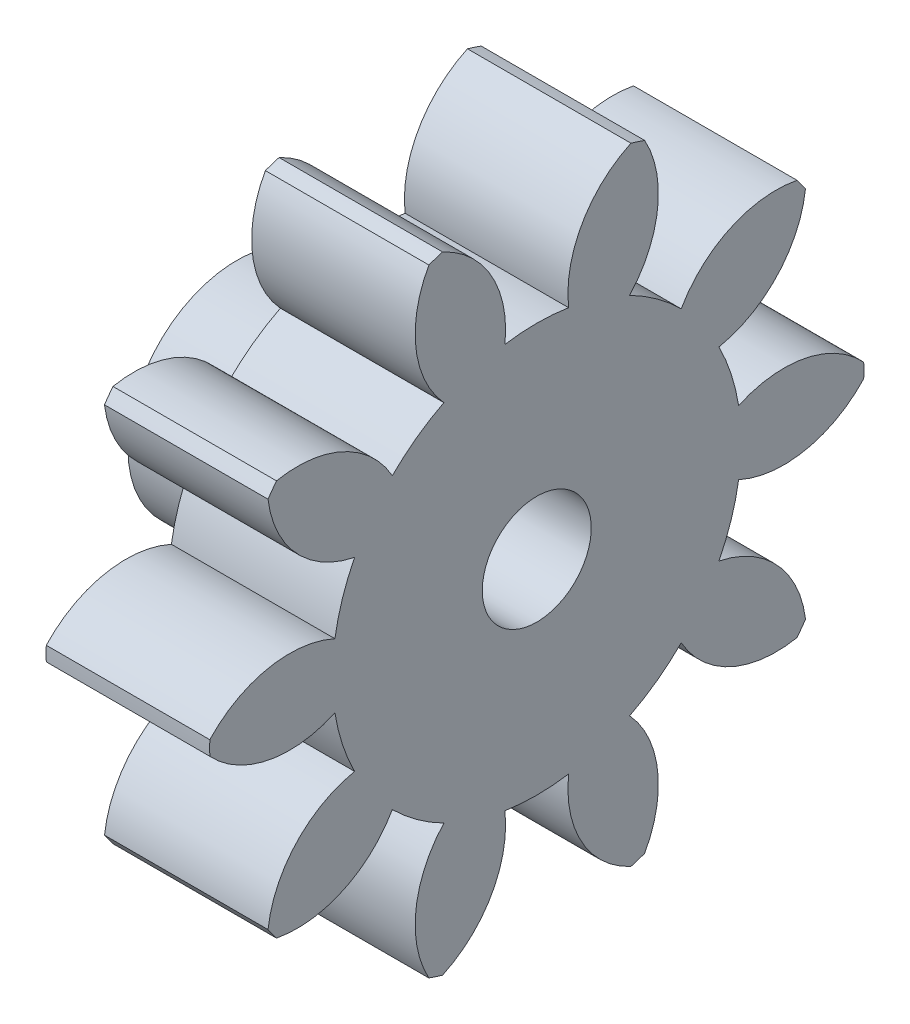
SolidWorks part; units mm, degrees
ref_plane "Plane1" through (0, 0, 0) normal (0, 0, 1) x (1, 0, 0)
ref_plane "Plane2" through (0, 0, 0) normal (0, 1, 0) x (1, 0, 0)
ref_plane "Plane3" through (0, 0, 0) normal (1, 0, 0) x (0, 0, -1)
sketch "HoldingSke" plane through (0, 0, 0) normal (0, 1, 0) x (1, 0, 0)
  line L0 (0, 0) -> (0.2462, -0.0434)
  line L1 (-15, 0) -> (100, 0) construction
  line L2 (0, 0) -> (-2.1039, 2.3779)
  line L3 (0, 0) -> (-11.863, 4.5341)
  line L4 (0, 0) -> (8.5048, 1.4996)
  line L5 (0, 0) -> (-9.3695, -3.4946)
  line L6 (0, 0) -> (-9.9476, -6.7116)
  line L7 (-2.1039, 2.3779) -> (0.4791, 14.0966)
  line L8 (-76.2, 54.61) -> (-74.8, 54.61)
  line L9 (-71.009, 38.7566) -> (-53.1078, 45.2721)
  line L10 (-76.2, 71.12) -> (104.1128, 71.12)
  line L11 (0, 0) -> (-12, 0)
  line L12 (-76.2, 101.6) -> (-76.073, 101.6)
  line L13 (24.9733, 27.94) -> (52.9518, 28.4284)
  line L14 (24.9733, 27.94) -> (24.9743, 27.94)
  line L15 (24.9733, 27.94) -> (100.4006, 29.5858)
  line L16 (-63.627, -4) -> (-12.827, -4)
  circle A0 centre (0, 0) radius 4
  circle A1 centre (0, 0) radius 8
  circle A2 centre (0, 0) radius 8
  circle A3 centre (0, 0) radius 4
  dimension "MHD" = 16
  dimension "Hub_dia" = 16
  dimension "Bore" = 8
  dimension "MBD" = 8
  dimension "Num_teeth" = 10
  dimension "Pitch" = 0.25
  dimension "Overall_len" = 10
  dimension "Show_teeth" = 10
  dimension "Thickness" = 12
  dimension "OAL" = 12.0001
  dimension "T_dim" = 1.4
  dimension "Ap" = 20
  dimension "H" = 19.05
  dimension "Pitch_radius" = 180.3128
  dimension "Width" = 12
  dimension "Backlash" = 0.127
  dimension "Addendum_fac" = 1
  dimension "Dedendum_fac" = 1.25
  dimension "Clearance_fac" = 0.25
  dimension "Dedendum_add" = 0.001
  dimension "Module" = 4
sketch "BasProSke" plane through (0, 0, 0) normal (0, 1, 0) x (1, 0, 0)
  line L0 (-10, 0) -> (60, 0) construction
  line L1 (0, 0) -> (0, 24)
  line L2 (0, 0) -> (12, 0)
  line L3 (12, 0) -> (12, 24)
  line L4 (12, 24) -> (0, 24)
  dimension "Thickness" = 12
  dimension "Diameter" = 48
revolve "Base-Revolve" add sketch "BasProSke" angle 360 about L0
sketch "TooCutSke" plane through (0, 0, 0) normal (1, 0, 0) x (0, 0, -1)
  line L1 (0, 0) -> (0, 107) construction
  line L2 (0, 0) -> (-3.3505, 19.7173) construction
  line L3 (0, 0) -> (-12.2295, 37.6384) construction
  line L4 (-3.3505, 19.7173) -> (-6.1147, 18.8192) construction
  arc A0 (2.338, 14.8157) -> (-2.338, 14.8157) centre (0, 0) ccw
  arc A1 (6.9466, 22.9992) -> (-6.9466, 22.9992) centre (0, 0) ccw
  circle A2 centre (0, 0) radius 20 construction
  circle A3 centre (0, 0) radius 18.7939 construction
  arc A4 (-2.338, 14.8157) -> (-6.9466, 22.9992) centre (-10.2857, 15.7294) ccw
  arc A5 (6.9466, 22.9992) -> (2.338, 14.8157) centre (10.2857, 15.7294) ccw
  dimension "Root_dia" = 29.998
  dimension "Overcut_dia" = 48.0508
  dimension "Pitch_dia" = 40
  dimension "Base_dia" = 37.5877
  dimension "Flank_rad" = 8
  dimension "Half_ang" = 18
  dimension "Half_CT" = 2.9064
extrude "ToothCut" cut sketch "TooCutSke" along normal through all
fillet "Breaks" [suppressed] radius 0.08
fillet "RootFillets" [suppressed] radius 1.001
pattern_circular "TeethCuts" count 10 every 36 about axis through (-10, 0, 0) along (1, 0, 0) of "ToothCut", "RootFillets", "Breaks"
sketch "HubNeaOneSke" plane through (0, 0, 0) normal (-1, 0, 0) x (0, 0, 1)
  circle A0 centre (0, 0) radius 8
  dimension "Diameter" = 16
extrude "HubNearOne" add sketch "HubNeaOneSke" along normal blind 38.0001
sketch "HubNeaBotSke" plane through (0, 0, 0) normal (-1, 0, 0) x (0, 0, 1)
  circle A0 centre (0, 0) radius 8
  dimension "Diameter" = 16
extrude "HubNearBoth" [suppressed] add sketch "HubNeaBotSke" along normal blind 19
ref_plane "FarPln" through (12, 0, 0) normal (1, 0, 0) x (0, 0, -1)
sketch "HubFarSke" plane through (12, 0, 0) normal (1, 0, 0) x (0, 0, -1)
  circle A0 centre (0, 0) radius 8
  dimension "Diameter" = 16
extrude "HubFar" [suppressed] add sketch "HubFarSke" along normal blind 19
sketch "BorSke" plane through (0, 0, 0) normal (1, 0, 0) x (0, 0, -1)
  circle A0 centre (0, 0) radius 4
  dimension "Diameter" = 8
extrude "Bore" cut sketch "BorSke" along normal mid plane 24.0001
sketch "KeySke" plane through (0, 0, 0) normal (1, 0, 0) x (0, 0, -1)
  line L0 (-1.5, 0) -> (-1.5, 5.4)
  line L1 (-1.5, 5.4) -> (1.5, 5.4)
  line L2 (1.5, 5.4) -> (1.5, 0)
  line L3 (0, 0) -> (0, 34) construction
  line L4 (-1.5, 0) -> (1.5, 0)
  dimension "Offset" = 5.4
  dimension "Width" = 3
extrude "Keyway" [suppressed] cut sketch "KeySke" along normal mid plane 24.0001
pattern_circular "Keyway2" [suppressed] count 2 every 90 about axis through (-10, 0, 0) along (1, 0, 0)
ref_plane "Plane4" through (-10, 0, 0) normal (-1, 0, 0) x (0, 0, 1)
sketch "Sketch1" plane through (-10, 0, 0) normal (-1, 0, 0) x (0, 0, 1)
  circle A0 centre (0, 0) radius 10.2707
extrude "Cut-Extrude1" cut sketch "Sketch1" along normal blind 43
equation "' \"Module@HoldingSke\" = 6.35"
equation "' \"Num_teeth@HoldingSke\" = 12"
equation "' \"Ap@HoldingSke\" =  20"
equation "' \"Ap@HoldingSke\" = 20"
equation "' \"Width@HoldingSke\" = 0.5 * 25.4"
equation "' \"Hub_dia@HoldingSke\"= 1 * 25.4"
equation "' \"Hub_dia@HoldingSke\" = 1 * 25.4"
equation "' \"Overall_len@HoldingSke\" = 1.0 * 25.4"
equation "' \"Bore@HoldingSke\" = 0.75 * 25.4"
equation "' \"T_dim@HoldingSke\" = 0.1 * 25.4"
equation "' \"Width@KeySke\" = 0.25 * 25.4"
equation "' \"Show_teeth@HoldingSke\" = 13"
equation "' \"Backlash@HoldingSke\" = 0.009 * 25.4"
equation "' \"Addendum_fac@HoldingSke\" = 1.0"
equation "' \"Dedendum_fac@HoldingSke\" = 1.25"
equation "' \"Dedendum_add@HoldingSke\" = 0.00005 * 25.4"
equation "' \"Clearance_fac@HoldingSke\" = 0.25"
equation "\"Pitch@HoldingSke\" = 1 / \"Module@HoldingSke\""
equation "\"Overcut_dia@TooCutSke\" = (\"Num_teeth@HoldingSke\" + 2 * \"Addendum_fac@HoldingSke\") / \"Pitch@HoldingSke\" + 0.002 * 25.4"
equation "\"Pitch_dia@TooCutSke\" = \"Num_teeth@HoldingSke\" / \"Pitch@HoldingSke\""
equation "\"Base_dia@TooCutSke\" = \"Num_teeth@HoldingSke\" / \"Pitch@HoldingSke\" * cos((\"Ap@HoldingSke\"  * 3.14159265 / 180))"
equation "\"Root_dia@TooCutSke\" = (\"Num_teeth@HoldingSke\" + 2) / \"Pitch@HoldingSke\" - 2 * (\"Addendum_fac@HoldingSke\" + \"Dedendum_fac@HoldingSke\") / \"Pitch@HoldingSke\" - \"Dedendum_add@HoldingSke\" * 2"
equation "\"Half_ang@TooCutSke\" = 180 / \"Num_teeth@HoldingSke\""
equation "\"Half_CT@TooCutSke\" = \"Num_teeth@HoldingSke\" / \"Pitch@HoldingSke\" * sin((3.14159265 / 2 / \"Num_teeth@HoldingSke\")) / 2 - 7 * \"Backlash@HoldingSke\" / 4"
equation "\"Flank_rad@TooCutSke\" = \"Num_teeth@HoldingSke\" / \"Pitch@HoldingSke\" / 5"
equation "\"Radius@RootFillets\" = \"Clearance_fac@HoldingSke\" / \"Pitch@HoldingSke\" + \"Dedendum_add@HoldingSke\""
equation "\"Break_rad@Breaks\" = 0.02 / \"Pitch@HoldingSke\""
equation "\"Thickness@HoldingSke\" = \"Width@HoldingSke\""
equation "\"OAL@HoldingSke\" = \"Thickness@HoldingSke\""
equation "\"MHD@HoldingSke\" = (\"Num_teeth@HoldingSke\" + 2) / \"Pitch@HoldingSke\" - 2 * (\"Addendum_fac@HoldingSke\" + \"Dedendum_fac@HoldingSke\")  / \"Pitch@HoldingSke\" - \"Dedendum_add@HoldingSke\" * 2"
equation "\"MBD@HoldingSke\" = (\"Num_teeth@HoldingSke\" + 2) / \"Pitch@HoldingSke\" - 2 * (\"Addendum_fac@HoldingSke\" + \"Dedendum_fac@HoldingSke\")  / \"Pitch@HoldingSke\" - \"Dedendum_add@HoldingSke\" * 2 - 0.002 * 25.4"
equation "\"MHD@HoldingSke\" = ((sgn( \"MHD@HoldingSke\" - \"Hub_dia@HoldingSke\" )-1)*( \"MHD@HoldingSke\" - \"Hub_dia@HoldingSke\" ))/-2+ \"Hub_dia@HoldingSke\""
equation "\"MBD@HoldingSke\" = ((sgn( \"MBD@HoldingSke\" - \"Bore@HoldingSke\" )-1)*( \"MBD@HoldingSke\" - \"Bore@HoldingSke\" ))/-2+ \"Bore@HoldingSke\""
equation "\"OAL@HoldingSke\" = ((sgn( \"OAL@HoldingSke\" - \"Overall_len@HoldingSke\" )+1)*( \"OAL@HoldingSke\" - \"Overall_len@HoldingSke\" ))/2 + \"Overall_len@HoldingSke\" + 0.000002 * 25.4"
equation "\"Num_teeth@TeethCuts\" = int( \"Show_teeth@HoldingSke\" ) + 1"
equation "\"Num_teeth@TeethCuts\" = ((sgn( \"Num_teeth@TeethCuts\" - \"Num_teeth@HoldingSke\" )-1)*( \"Num_teeth@TeethCuts\" - \"Num_teeth@HoldingSke\" ))/-2+ \"Num_teeth@HoldingSke\""
equation "\"Num_teeth@TeethCuts\" = ((sgn( \"Num_teeth@TeethCuts\" - 2.0)+1)*( \"Num_teeth@TeethCuts\" - 2.0))/2 +2.0"
equation "\"Angle@TeethCuts\" = 360.0 / \"Num_teeth@HoldingSke\""
equation "\"Diameter@BasProSke\" = (\"Num_teeth@HoldingSke\" + 2 * \"Addendum_fac@HoldingSke\") / \"Pitch@HoldingSke\""
equation "\"Thickness@BasProSke\"  = \"Thickness@HoldingSke\""
equation "' \"Fillet_rad@BasProSke\" =  \"Thickness@HoldingSke\" * 0.05"
equation "' \"Fillet_rad@BasProSke\" = \"Thickness@HoldingSke\" * 0.05"
equation "\"MHD@HoldingSke\" = ((sgn( \"MHD@HoldingSke\" - \"Root_dia@TooCutSke\" )-1)*( \"MHD@HoldingSke\" - \"Root_dia@TooCutSke\" ))/-2+ \"Root_dia@TooCutSke\""
equation "\"Diameter@HubNeaOneSke\" = \"MHD@HoldingSke\""
equation "\"Length@HubNearOne\" = \"OAL@HoldingSke\" - \"Thickness@BasProSke\""
equation "\"Diameter@HubNeaBotSke\" = \"MHD@HoldingSke\""
equation "\"Length@HubNearBoth\" = ( \"OAL@HoldingSke\" - \"Thickness@BasProSke\" ) / 2.0"
equation "\"Thickness@FarPln\" = \"Thickness@BasProSke\""
equation "\"Diameter@HubFarSke\" = \"MHD@HoldingSke\""
equation "\"Length@HubFar\" = ( \"OAL@HoldingSke\" - \"Thickness@BasProSke\" ) / 2.0"
equation "\"Diameter@BorSke\" = \"MBD@HoldingSke\""
equation "\"D1@Bore\" = \"OAL@HoldingSke\" * 2.0"
equation "\"D1@Keyway\" = \"OAL@HoldingSke\" * 2.0"
equation "\"Offset@KeySke\" = \"T_dim@HoldingSke\" + \"MBD@HoldingSke\" / 2.0"
